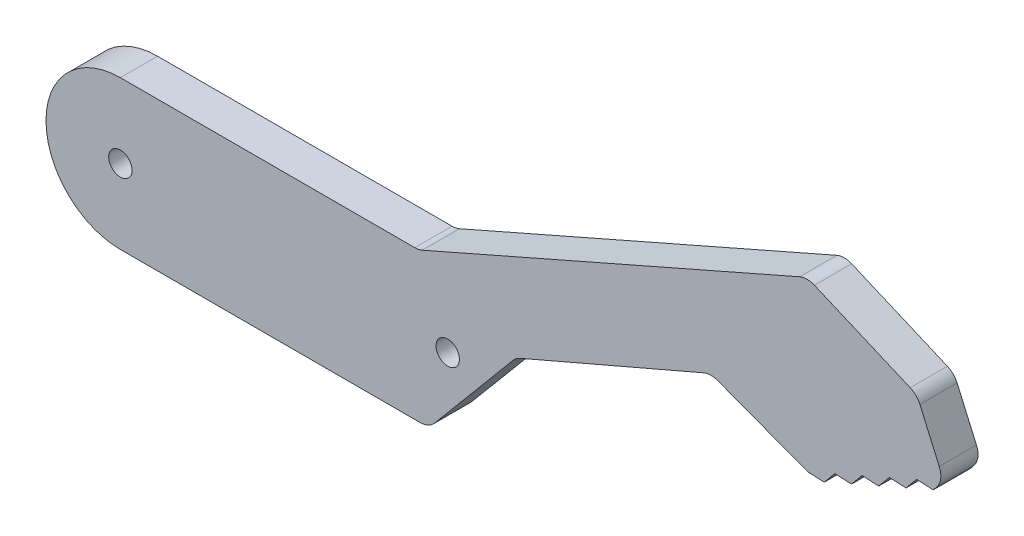
SolidWorks part; units mm, degrees
ref_plane "Front Plane" through (0, 0, 0) normal (0, 0, 1) x (1, 0, 0)
ref_plane "Top Plane" through (0, 0, 0) normal (0, 1, 0) x (1, 0, 0)
ref_plane "Right Plane" through (0, 0, 0) normal (1, 0, 0) x (0, 0, -1)
sketch "Sketch1" plane through (0, 0, 0) normal (0, 0, 1) x (1, 0, 0)
  line L0 (0, 0) -> (88, 0) construction
  line L1 (0, 20) -> (88, 20)
  line L2 (0, -20) -> (88, -20)
  line L3 (80.2, 20) -> (96.852, -17.9344) construction
  line L4 (80.2, 20) -> (204.7301, 74.6649) construction
  line L5 (96.852, -17.9344) -> (221.3821, 36.7305) construction
  line L6 (204.7301, 74.6649) -> (221.3821, 36.7305) construction
  line L7 (80.2, 20) -> (184.5855, 65.822)
  line L8 (184.5855, 65.822) -> (214.1471, 53.2125)
  line L9 (214.1471, 53.2125) -> (221.3821, 36.7305)
  line L10 (221.3821, 36.7305) -> (184.7556, 20.6526) construction
  line L11 (184.7556, 20.6526) -> (158.662, 30.4914)
  line L12 (158.662, 30.4914) -> (106.3633, 7.924)
  line L13 (184.7556, 20.6526) -> (189.2222, 20.4291)
  line L14 (189.2222, 20.4291) -> (192.0809, 23.8682)
  line L15 (106.3633, 7.924) -> (82.9405, -20)
  line L16 (192.0809, 23.8682) -> (196.5475, 23.6447)
  line L17 (196.5475, 23.6447) -> (199.4062, 27.0838)
  line L18 (199.4062, 27.0838) -> (203.8728, 26.8602)
  line L19 (203.8728, 26.8602) -> (206.7315, 30.2994)
  line L20 (206.7315, 30.2994) -> (211.1981, 30.0758)
  line L21 (211.1981, 30.0758) -> (214.0568, 33.5149)
  line L22 (214.0568, 33.5149) -> (218.5234, 33.2914)
  line L23 (218.5234, 33.2914) -> (221.3821, 36.7305)
  arc A0 (0, 20) -> (0, -20) centre (0, 0) ccw
  arc A1 (88, -20) -> (88, 20) centre (88, 0) ccw
  circle A2 centre (0, 0) radius 3.15
  circle A3 centre (88, 0) radius 3.15
  point P3 (44, 0)
  dimension "D11" = 6.3
  dimension "D1" = 40
  dimension "D2" = 88
  dimension "D3" = 156.3
  dimension "D4" = 7.8
  dimension "D5" = 136
  dimension "D6" = 56.96
  dimension "D7" = 40
  dimension "D8" = 18
  dimension "D9" = 22
  dimension "D10" = 136
  dimension "D12" = 8
  dimension "D13" = 2
extrude "Boss-Extrude1" add sketch "Sketch1" along normal blind 10 contours A1 L1 A0 L2 A3 A2 | A1 L12 L11 L10 L9 L8 L7 L1
fillet "Fillet2" radius 5 8 edges at (184.7556, 20.6526, 5) (158.662, 30.4914, 5) (106.3633, 7.924, 5) (82.9405, -20, 5) (80.2, 20, 5) (184.5855, 65.822, 5) (214.1471, 53.2125, 5) (221.3821, 36.7305, 5)
